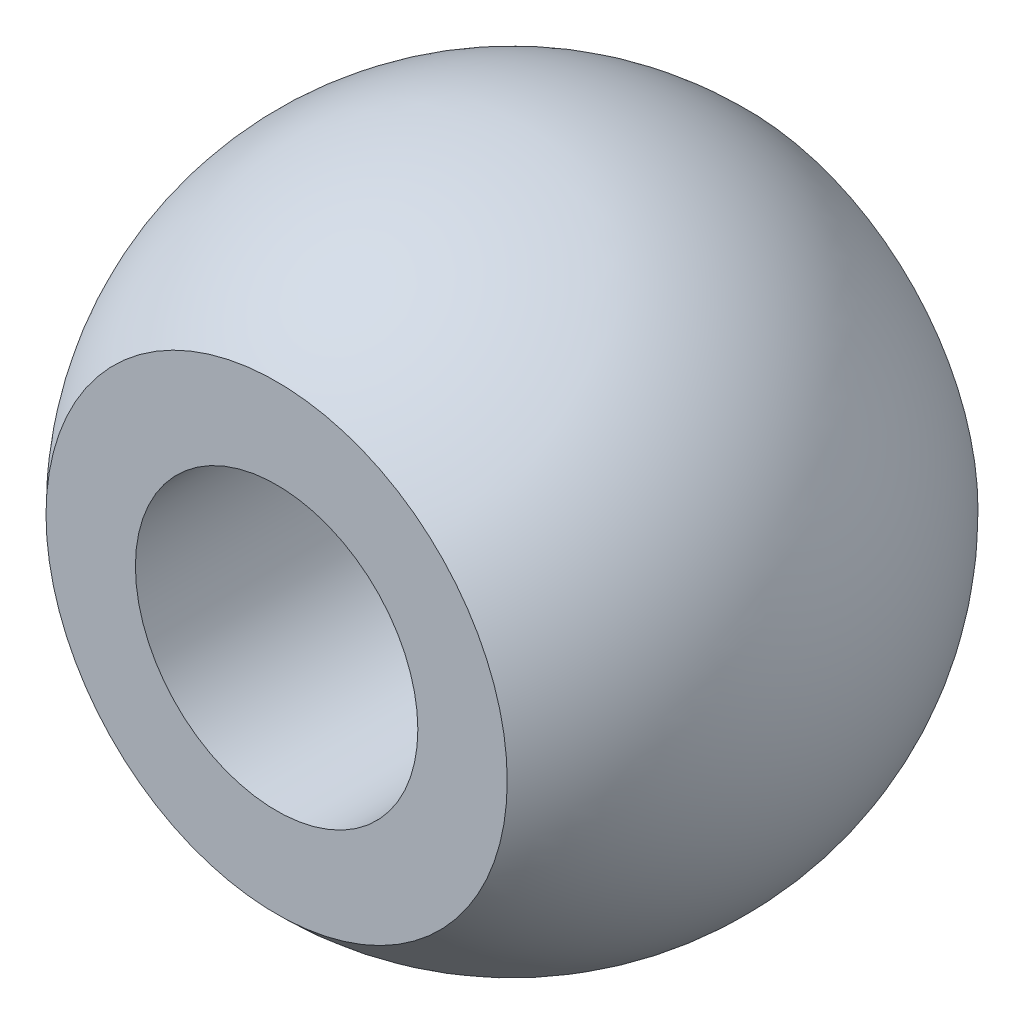
SolidWorks part; units mm, degrees
ref_plane "正面" through (0, 0, 0) normal (0, 0, 1) x (1, 0, 0)
ref_plane "平面" through (0, 0, 0) normal (0, 1, 0) x (1, 0, 0)
ref_plane "右側面" through (0, 0, 0) normal (1, 0, 0) x (0, 0, -1)
sketch "ｽｹｯﾁ1" plane through (0, 0, 0) normal (0, 0, 1) x (1, 0, 0)
  line L0 (0, 3.5) -> (0, -3.5)
  arc A0 (0, 3.5) -> (0, -3.5) centre (0, 0) cw
  point P4 (0, 5.0717)
  point P5 (0, 0)
  dimension "D1" = 3.5
revolve "回転1" add sketch "ｽｹｯﾁ1" angle 360 about L0
ref_plane "平面1" through (0, 0, 2.5) normal (0, 0, 1) x (1, 0, 0)
sketch "ｽｹｯﾁ3" plane through (0, 0, 2.5) normal (0, 0, 1) x (1, 0, 0)
  line L1 (-5.7023, 5.2357) -> (6.2116, 5.2357)
  line L2 (-5.7023, 5.2357) -> (-5.7023, -4.826)
  line L3 (-5.7023, -4.826) -> (6.2116, -4.826)
  line L4 (6.2116, 5.2357) -> (6.2116, -4.826)
  point P4 (-5.7023, 5.2357)
extrude "ｶｯﾄ - 押し出し1" cut sketch "ｽｹｯﾁ3" along normal blind 10
mirror "ﾐﾗｰ1" about plane through (0, 0, 0) normal (0, 0, 1) of "ｶｯﾄ - 押し出し1"
sketch "ｽｹｯﾁ4" plane through (0, 0, 0) normal (0, 0, 1) x (1, 0, 0)
  circle A0 centre (0, 0) radius 1.5
  dimension "D1" = 3
extrude "ｶｯﾄ - 押し出し2" cut sketch "ｽｹｯﾁ4" against normal through all both and the other way through all
